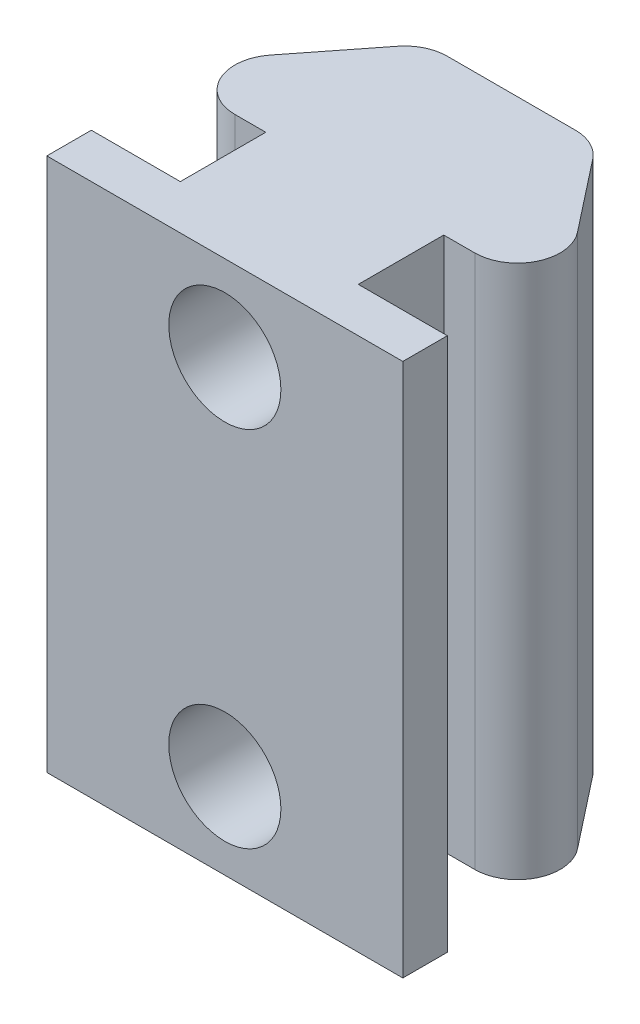
SolidWorks part; units mm, degrees
ref_plane "Front Plane" through (0, 0, 0) normal (0, 0, 1) x (1, 0, 0)
ref_plane "Top Plane" through (0, 0, 0) normal (0, 1, 0) x (1, 0, 0)
ref_plane "Right Plane" through (0, 0, 0) normal (1, 0, 0) x (0, 0, -1)
sketch "Sketch1" plane through (0, 0, 0) normal (0, 0, 1) x (1, 0, 0)
  line L0 (-6.35, 0) -> (6.35, 0) construction
  line L1 (-6.35, -9.525) -> (6.35, -9.525)
  line L2 (-6.35, -9.525) -> (-6.35, 9.525)
  line L3 (-6.35, 9.525) -> (6.35, 9.525)
  line L4 (6.35, -9.525) -> (6.35, 9.525)
  line L5 (-6.35, -9.525) -> (6.35, 9.525) construction
  line L6 (-6.35, 9.525) -> (6.35, -9.525) construction
  line L8 (-6.35, 9.525) -> (0, 9.525)
  point P0 (0, 0)
  dimension "D1" = 19.05
  dimension "D2" = 12.7
extrude "Boss-Extrude1" add sketch "Sketch1" along normal blind 1.5875 contours L2 L1 L4 L3
sketch "Sketch2" plane through (0, 9.525, 0) normal (0, 1, 0) x (1, 0, 0)
  line L0 (0, 0) -> (0, 8.636) construction
  line L1 (3.175, 0) -> (3.175, 3.048)
  line L2 (-6.35, 0) -> (6.35, 0) construction
  line L3 (3.175, 3.048) -> (4.2815, 3.048)
  line L4 (5.4799, 5.5135) -> (3.4844, 8.0535)
  line L5 (2.286, 8.636) -> (-2.286, 8.636)
  line L6 (3.175, 0) -> (-3.175, 0)
  line L7 (-3.175, 0) -> (-3.175, 3.048)
  line L8 (-3.175, 3.048) -> (-4.2815, 3.048)
  line L9 (-5.4799, 5.5135) -> (-3.4844, 8.0535)
  arc A0 (3.4844, 8.0535) -> (2.286, 8.636) centre (2.286, 7.112) ccw
  arc A1 (4.2815, 3.048) -> (5.4799, 5.5135) centre (4.2815, 4.572) ccw
  arc A2 (-4.2815, 3.048) -> (-5.4799, 5.5135) centre (-4.2815, 4.572) cw
  arc A3 (-3.4844, 8.0535) -> (-2.286, 8.636) centre (-2.286, 7.112) cw
  point P7 (1.7729, 8.636)
  point P10 (3.175, 2.794)
  point P19 (3.0268, 8.636)
  point P22 (7.4168, 3.048)
  point P25 (-7.4168, 3.048)
  point P28 (-3.0268, 8.636)
  dimension "D5" = 1.524
  dimension "D1" = 8.636
  dimension "D2" = 6.35
  dimension "D3" = 5.588
  dimension "D4" = 14.8336
  dimension "D6" = 4.572
extrude "Boss-Extrude2" add sketch "Sketch2" against normal up to surface (19.05 mm away) up to face at (0, -9.525, 0.7937)
sketch "Sketch4" plane through (0, 0, 1.5875) normal (0, 0, 1) x (1, 0, 0)
  line L0 (-6.35, 0) -> (6.35, 0) construction
  line L1 (-6.35, -9.525) -> (-6.35, 9.525) construction
  line L2 (6.35, -9.525) -> (6.35, 9.525) construction
  line L3 (-6.35, 9.525) -> (6.35, 9.525) construction
  circle A0 centre (0, 6.477) radius 2
  circle A1 centre (0, -6.477) radius 2
  dimension "D1" = 4
  dimension "D2" = 3.048
extrude "Cut-Extrude1" cut sketch "Sketch4" against normal up to surface (4.6355 mm away) up to face at (3.7282, 0, -3.048)
